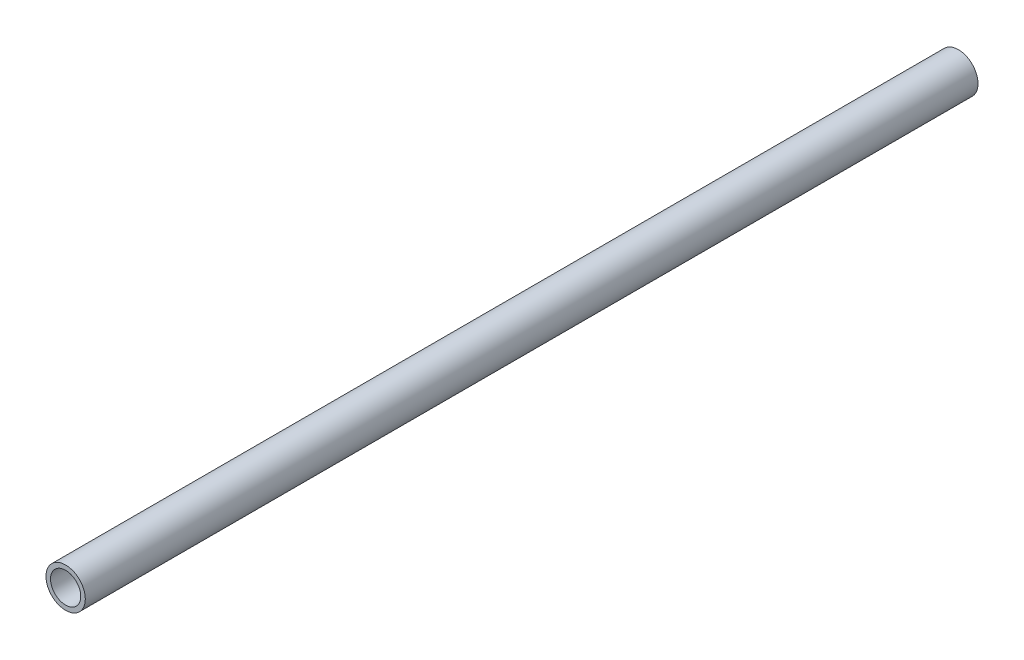
SolidWorks part; units mm, degrees
material "AISI 4130 Steel, annealed at 865C"
ref_plane "X-Y Datum" through (0, 0, 0) normal (0, 0, 1) x (1, 0, 0)
ref_plane "X-Z Datum" through (0, 0, 0) normal (0, 1, 0) x (1, 0, 0)
ref_plane "Y-Z Datum" through (0, 0, 0) normal (1, 0, 0) x (0, 0, -1)
sketch "Sketch1" plane through (0, 0, 0) normal (0, 0, 1) x (1, 0, 0)
  circle A0 centre (0, 0) radius 4.8768
  circle A1 centre (0, 0) radius 6.35
  dimension "D1" = 12.7
  dimension "D2" = 1.4732
extrude "Boss-Extrude1" add sketch "Sketch1" along normal up to surface (288.29 mm away)
